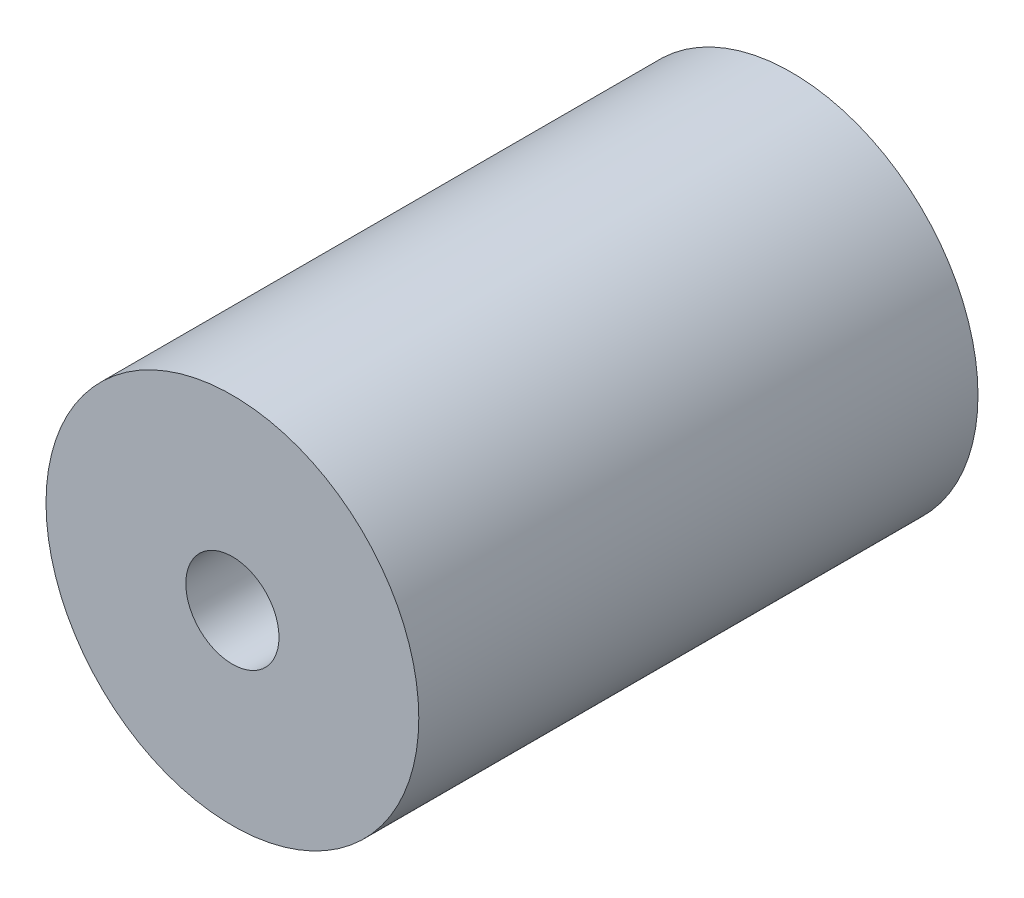
SolidWorks part; units mm, degrees
material "PE Высокой плотности"
ref_plane "Front" through (0, 0, 0) normal (0, 0, 1) x (1, 0, 0)
ref_plane "Top" through (0, 0, 0) normal (0, 1, 0) x (1, 0, 0)
ref_plane "Side" through (0, 0, 0) normal (1, 0, 0) x (0, 0, -1)
sketch "PipeSketch" plane through (0, 0, 0) normal (0, 0, 1) x (1, 0, 0)
  circle A0 centre (0, 0) radius 2.5
  circle A1 centre (0, 0) radius 10
  dimension "OuterDiameter" = 5
  dimension "InnerDiameter" = 20
extrude "Extrusion" add sketch "PipeSketch" along normal blind 30
sketch "FilterSketch" plane through (0, 0, 0) normal (0, 0, 1) x (1, 0, 0)
  circle A0 centre (0, 0) radius 10 construction
  dimension "NominalDiameter" = 20
